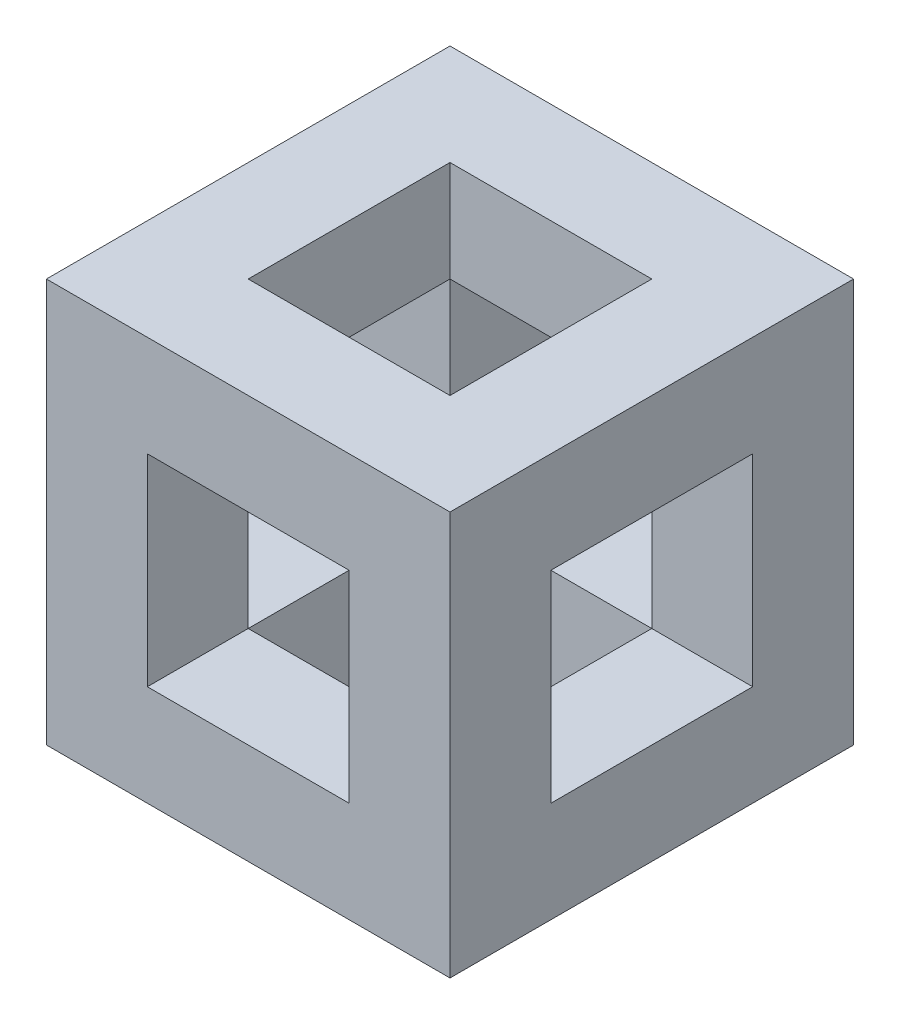
SolidWorks part; units mm, degrees
ref_plane "Front Plane" through (0, 0, 0) normal (0, 0, 1) x (1, 0, 0)
ref_plane "Top Plane" through (0, 0, 0) normal (0, 1, 0) x (1, 0, 0)
ref_plane "Right Plane" through (0, 0, 0) normal (1, 0, 0) x (0, 0, -1)
sketch "Sketch2" plane through (0, 0, 0) normal (0, 0, 1) x (1, 0, 0)
  line L1 (25, -25) -> (-25, -25)
  line L2 (25, -25) -> (25, 25)
  line L3 (25, 25) -> (-25, 25)
  line L4 (-25, -25) -> (-25, 25)
  line L5 (25, -25) -> (-25, 25) construction
  line L6 (25, 25) -> (-25, -25) construction
  point P0 (0, 0)
  dimension "D1" = 50
  dimension "D2" = 50
extrude "Boss-Extrude1" add sketch "Sketch2" along normal blind 50
sketch "Sketch3" plane through (0, 25, 0) normal (0, 1, 0) x (1, 0, 0)
  line L0 (-25, -50) -> (-25, 0) construction
  line L1 (12.5, -37.5) -> (-12.5, -37.5)
  line L2 (12.5, -37.5) -> (12.5, -12.5)
  line L3 (12.5, -12.5) -> (-12.5, -12.5)
  line L4 (-12.5, -37.5) -> (-12.5, -12.5)
  line L5 (12.5, -37.5) -> (-12.5, -12.5) construction
  line L6 (12.5, -12.5) -> (-12.5, -37.5) construction
  line L8 (25, -50) -> (-25, -50) construction
  point P0 (0, -25)
  point P9 (0.2953, -24.2201)
  point P10 (0, 0)
  point P11 (0, 0)
  dimension "D1" = 25
  dimension "D2" = 25
  dimension "D3" = 25
  dimension "D4" = 25
extrude "Cut-Extrude1" cut sketch "Sketch3" against normal through all contours L2 L1 L4 L3
sketch "Sketch4" plane through (0, 0, 50) normal (0, 0, 1) x (1, 0, 0)
  line L1 (-12.5, -12.5) -> (12.5, -12.5)
  line L2 (-12.5, -12.5) -> (-12.5, 12.5)
  line L3 (-12.5, 12.5) -> (12.5, 12.5)
  line L4 (12.5, -12.5) -> (12.5, 12.5)
  line L5 (-12.5, -12.5) -> (12.5, 12.5) construction
  line L6 (-12.5, 12.5) -> (12.5, -12.5) construction
  point P0 (0, 0)
  point P6 (0, 0)
  dimension "D1" = 25
  dimension "D2" = 25
extrude "Cut-Extrude2" cut sketch "Sketch4" against normal through all
sketch "Sketch5" plane through (25, 0, 0) normal (1, 0, 0) x (0, 0, -1)
  line L0 (-50, -25) -> (-50, 25) construction
  line L1 (-12.5, -12.5) -> (-37.5, -12.5)
  line L2 (-12.5, -12.5) -> (-12.5, 12.5)
  line L3 (-12.5, 12.5) -> (-37.5, 12.5)
  line L4 (-37.5, -12.5) -> (-37.5, 12.5)
  line L5 (-12.5, -12.5) -> (-37.5, 12.5) construction
  line L6 (-12.5, 12.5) -> (-37.5, -12.5) construction
  line L7 (-50, 25) -> (0, 25) construction
  point P0 (-25, 0)
  dimension "D1" = 25
  dimension "D2" = 25
  dimension "D3" = 25
  dimension "D4" = 25
extrude "Cut-Extrude3" cut sketch "Sketch5" against normal through all contours L2 L1 L4 L3
